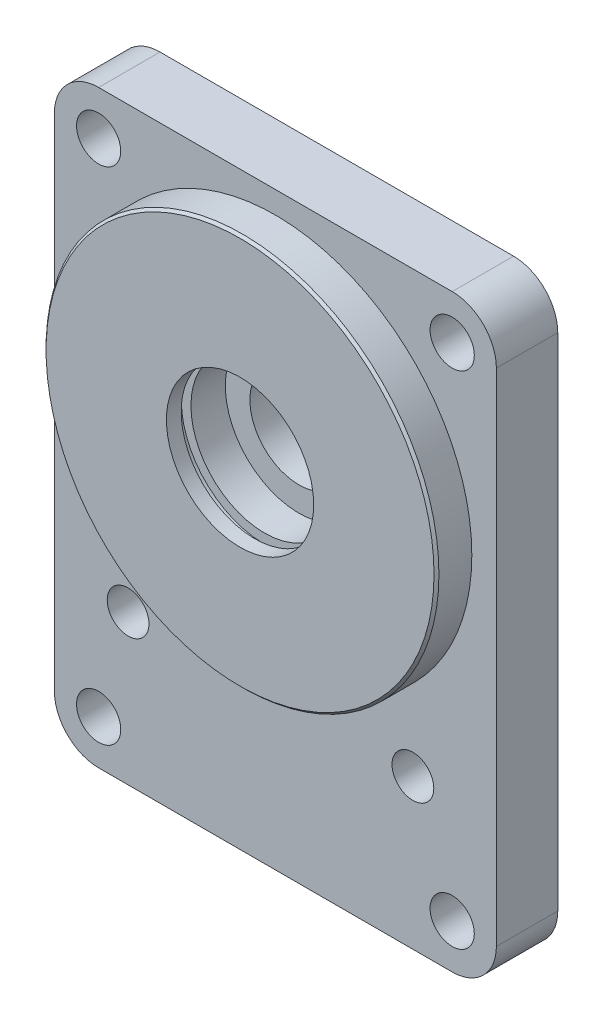
SolidWorks part; units mm, degrees
ref_plane "Ön Düzlem" through (0, 0, 0) normal (0, 0, 1) x (1, 0, 0)
ref_plane "Üst Düzlem" through (0, 0, 0) normal (0, 1, 0) x (1, 0, 0)
ref_plane "Sağ Düzlem" through (0, 0, 0) normal (1, 0, 0) x (0, 0, -1)
sketch "Çizim1" plane through (0, 0, 0) normal (0, 0, 1) x (1, 0, 0)
  line L1 (36, -60) -> (-36, -60)
  line L2 (45, -51) -> (45, 51)
  line L3 (36, 60) -> (-36, 60)
  line L4 (-45, -51) -> (-45, 51)
  line L5 (45, -60) -> (-45, 60) construction
  line L6 (45, 60) -> (-45, -60) construction
  arc A0 (-45, -51) -> (-36, -60) centre (-36, -51) ccw
  arc A1 (36, -60) -> (45, -51) centre (36, -51) ccw
  arc A2 (45, 51) -> (36, 60) centre (36, 51) ccw
  arc A3 (-36, 60) -> (-45, 51) centre (-36, 51) ccw
  circle A4 centre (-36, 51) radius 4.5
  circle A5 centre (36, 51) radius 4.5
  circle A6 centre (36, -51) radius 4.5
  circle A7 centre (-36, -51) radius 4.5
  point P0 (0, 0)
  dimension "D3" = 9
  dimension "D4" = 9
  dimension "D1" = 120
  dimension "D2" = 90
  dimension "D5" = 36
extrude "Yükseklik-Ekstrüzyon1" add sketch "Çizim1" along normal mid plane 12.5
sketch "Çizim2" plane through (0, 0, 6.25) normal (0, 0, 1) x (1, 0, 0)
  line L0 (0, 0) -> (0, 22.3355) construction
  circle A0 centre (0, 15.5) radius 40
  dimension "D2" = 80
  dimension "D1" = 15.5
extrude "Yükseklik-Ekstrüzyon2" add sketch "Çizim2" along normal blind 7.2 contours A0
sketch "Çizim3" plane through (0, 0, 13.45) normal (0, 0, 1) x (1, 0, 0)
  circle A2 centre (0, 15.5) radius 10
  dimension "D1" = 20
extrude "Kes-Ekstrüzyon1" cut sketch "Çizim3" against normal up to surface (19.7 mm away) up to face at (0, 0, -6.25)
sketch "Çizim5" plane through (0, 0, -6.25) normal (0, 0, -1) x (-1, 0, 0)
  line L1 (-39.4013, 30.2675) -> (-39.4013, 29.0735)
  line L2 (-40.0789, 27.819) -> (-41.4013, 26.952)
  line L3 (-41.4013, 26.952) -> (-41.4013, -25.417)
  line L4 (41.2763, 27.819) -> (42.5987, 26.952)
  line L5 (40.5987, 30.2675) -> (40.5987, 29.0735)
  line L6 (42.5987, 26.952) -> (42.5987, -25.417)
  line L7 (-40.0789, -26.284) -> (-41.4013, -25.417)
  line L8 (-39.4013, -28.7325) -> (-39.4013, -27.5385)
  line L9 (40.5987, -28.7325) -> (40.5987, -27.5385)
  line L10 (41.2763, -26.284) -> (42.5987, -25.417)
  arc A4 (-27.6761, 42.005) -> (28.8735, 42.005) centre (0.5987, 0.7675) cw
  circle A5 centre (-28.4013, 30.2675) radius 5.1
  circle A6 centre (29.5987, 30.2675) radius 5.1
  arc A7 (-29.8466, 41.1721) -> (-39.4013, 30.2675) centre (-28.4013, 30.2675) ccw
  arc A8 (31.044, 41.1721) -> (40.5987, 30.2675) centre (29.5987, 30.2675) cw
  arc A9 (-39.4013, 29.0735) -> (-40.0789, 27.819) centre (-40.9013, 29.0735) cw
  arc A10 (-27.6761, 42.005) -> (-29.8466, 41.1721) centre (-30.5036, 46.1288) cw
  arc A11 (28.8735, 42.005) -> (31.044, 41.1721) centre (31.701, 46.1288) ccw
  arc A12 (40.5987, 29.0735) -> (41.2763, 27.819) centre (42.0987, 29.0735) ccw
  arc A13 (31.044, 41.1721) -> (40.5987, 30.2675) centre (29.5987, 30.2675) cw
  arc A14 (-27.6761, -40.47) -> (28.8735, -40.47) centre (0.5987, 0.7675) ccw
  arc A15 (-27.6761, -40.47) -> (-29.8466, -39.6371) centre (-30.5036, -44.5938) ccw
  arc A16 (-39.4013, -27.5385) -> (-40.0789, -26.284) centre (-40.9013, -27.5385) ccw
  arc A17 (-29.8466, -39.6371) -> (-39.4013, -28.7325) centre (-28.4013, -28.7325) cw
  circle A18 centre (-28.4013, -28.7325) radius 5.1
  arc A19 (31.044, -39.6371) -> (40.5987, -28.7325) centre (29.5987, -28.7325) ccw
  arc A20 (40.5987, -27.5385) -> (41.2763, -26.284) centre (42.0987, -27.5385) cw
  arc A21 (28.8735, -40.47) -> (31.044, -39.6371) centre (31.701, -44.5938) cw
  arc A22 (31.044, -39.6371) -> (40.5987, -28.7325) centre (29.5987, -28.7325) ccw
  circle A23 centre (29.5987, -28.7325) radius 5.1
  point P1 (0, 0)
  point P3 (0, 0)
  point P10 (0.5987, 0.7675)
  point P13 (0.5987, 0.7675)
  point P21 (-28.7296, -39.7276)
  point P45 (-41.4013, 0.7675)
  point P57 (42.5987, 0.7675)
  circle M7 centre (0, 15.5) radius 10
  dimension "D5" = 10.2
  dimension "D8" = 50
  dimension "D9" = 11
  dimension "D10" = 1.5
  dimension "D11" = 5
  dimension "D6" = 58
  dimension "D7" = 29.5
extrude "Yükseklik-Ekstrüzyon4" add sketch "Çizim5" along normal blind 3 contours A5 | A6 | A23 | A18 | A14 A21 A19 L9 A20 L10 L6 L4 A12 L5 A8 A11 A4 A10 A7 L1 A9 L2 L3 L7 A16 L8 A17 A15 A5 A6 A18 A23 M7
fillet "Radyus1" radius 1 24 edges at (-29.9097, -39.9257, -6.25) (-37.8721, -35.9817, -6.25) (-40.5987, -28.1355, -6.25) (-40.7789, -26.8256, -6.25) (-41.9375, -25.8505, -6.25) (-41.9375, 27.3855, -6.25) (-40.7789, 28.3606, -6.25) (-40.5987, 29.6705, -6.25) (-37.8721, 37.5167, -6.25) (-29.9097, 41.4607, -6.25) (-0.5987, 50.7675, -6.25) (28.7123, 41.4607, -6.25) (36.6747, 37.5167, -6.25) (39.4013, 29.6705, -6.25) (39.5815, 28.3606, -6.25) (40.7401, 27.3855, -6.25) (41.4013, 0.7675, -6.25) (40.7401, -25.8505, -6.25) (39.5815, -26.8256, -6.25) (39.4013, -28.1355, -6.25) (36.6747, -35.9817, -6.25) (28.7123, -39.9257, -6.25) (-0.5987, -49.2325, -6.25) (-42.5987, 0.7675, -6.25)
hole_wizard "M10 Dişli Delik1" positions "Çizim6" profile "Çizim7" tap size "M10" standard "ISO"
sketch "Çizim6" plane through (0, 0, -9.25) normal (0, 0, -1) x (-1, 0, 0)
  point P0 (-28, 29.5)
  point P2 (30, 29.5)
  point P4 (30, -29.5)
  point P6 (-28, -29.5)
  point P11 (0, 0)
  point P12 (0, 0)
  point P13 (0, 0)
  point P14 (0, 0)
  dimension "D1" = 58
  dimension "D2" = 28
  dimension "D3" = 59
  dimension "D4" = 29.5
sketch "Çizim7" plane through (28, 29.5, -9.25) normal (1, 0, 0) x (0, 1, 0)
  line L0 (0, 0) -> (0, 19.0537)
  line L1 (0, 19.0537) -> (4.25, 16.5)
  line L2 (4.25, 16.5) -> (4.25, 0.775)
  line L3 (4.25, 0.775) -> (5.025, 0)
  line L5 (5.025, 0) -> (0, 0)
  line L6 (-4.25, 0.775) -> (-5.025, 0) construction
  line L10 (0, 19.0537) -> (-4.25, 16.5) construction
  line L11 (0, -6.35) -> (0, 107.95) construction
  dimension "Tap Drill Dia." = 8.5
  dimension "Tap Drill Depth" = 16.5
  dimension "Near C'Sink Dia." = 10.05
  dimension "Near C'Sink Angle" = 90
  dimension "Drill Angle" = 118
cosmetic thread "Delik Dişi1" parameters "D1"=20, "D2"=10
cosmetic thread "Delik Dişi2" parameters "D1"=20, "D2"=10
cosmetic thread "Delik Dişi3" parameters "D1"=20, "D2"=10
cosmetic thread "Delik Dişi4" parameters "D1"=20, "D2"=10
sketch "Çizim8" plane through (0, 0, -6.25) normal (0, 0, -1) x (-1, 0, 0)
  circle A0 centre (-36, -51) radius 8
  circle A1 centre (36, -51) radius 8
  circle A2 centre (36, 51) radius 8
  circle A3 centre (-36, 51) radius 8
  dimension "D1" = 16
extrude "Kes-Ekstrüzyon2" cut sketch "Çizim8" against normal blind 0.5
sketch "Çizim9" plane through (0, 0, 13.45) normal (0, 0, 1) x (1, 0, 0)
  circle A0 centre (0, 15.5) radius 15
  dimension "D1" = 30
extrude "Kes-Ekstrüzyon3" cut sketch "Çizim9" against normal blind 12
sketch "Çizim12" plane through (0, 0, 0) normal (1, 0, 0) x (0, 0, -1)
  line L0 (-13.45, 55.5) -> (-13.45, -24.5) construction
  line L1 (-10.45, 32.4659) -> (-8.45, 32.4659)
  line L2 (-10.45, 32.4659) -> (-10.45, 27.4659)
  line L3 (-10.45, 27.4659) -> (-8.45, 27.4659)
  line L4 (-8.45, 32.4659) -> (-8.45, 27.4659)
  line L5 (23.6616, 15.5) -> (-36.1616, 15.5) construction
  point P9 (-6.25, 15.5)
  dimension "D1" = 2
  dimension "D2" = 5
  dimension "D3" = 3
revolve "Kes-Döndür1" cut sketch "Çizim12" angle 360 about L5
chamfer "Pah1" distance 0.5 angle 45 1 edges at (40, 15.5, 13.45)
